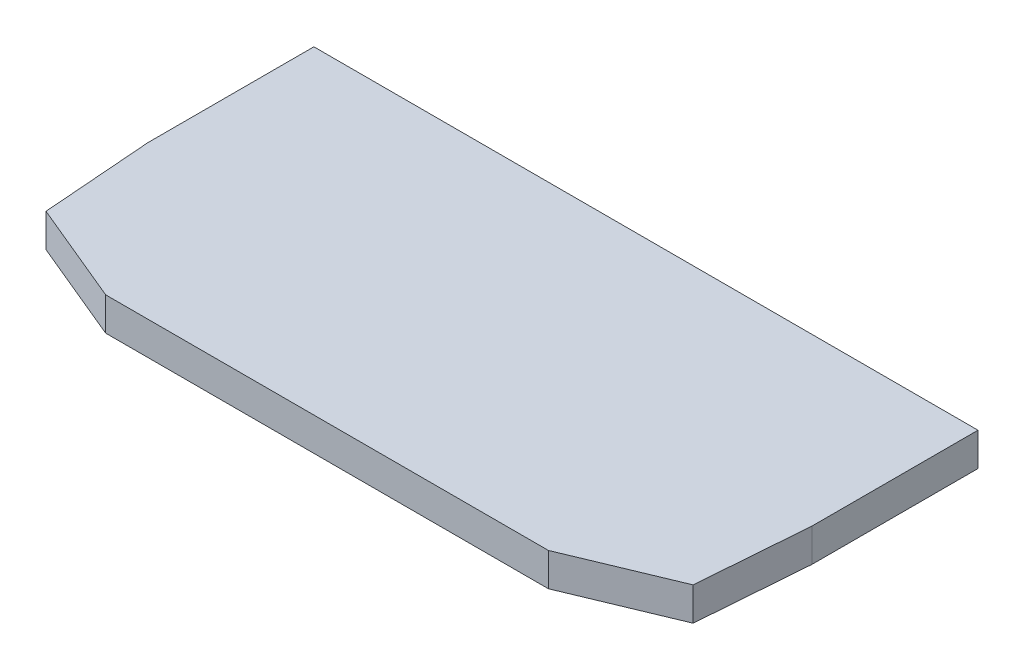
SolidWorks part; units mm, degrees
ref_plane "Front Plane" through (0, 0, 0) normal (0, 0, 1) x (1, 0, 0)
ref_plane "Top Plane" through (0, 0, 0) normal (0, 1, 0) x (1, 0, 0)
ref_plane "Right Plane" through (0, 0, 0) normal (1, 0, 0) x (0, 0, -1)
sketch "Sketch3" plane through (0, 0, 0) normal (0, 1, 0) x (1, 0, 0)
  line L0 (-27.1418, 11.12) -> (32.8582, 11.12)
  line L1 (32.8582, 11.12) -> (32.8582, -3.88)
  line L2 (-27.1418, 11.12) -> (-27.1418, -3.88)
  line L3 (-27.1418, -3.88) -> (-26.3741, -13.8504)
  line L4 (-26.3741, -13.8504) -> (-17.1418, -17.6929)
  line L5 (-17.1418, -17.6929) -> (22.8582, -17.6929)
  line L6 (22.8582, -17.6929) -> (32.0905, -13.8504)
  line L7 (32.0905, -13.8504) -> (32.8582, -3.88)
  dimension "D1" = 60
  dimension "D2" = 15
  dimension "D3" = 10
  dimension "D4" = 15
  dimension "D5" = 10
  dimension "D6" = 10
  dimension "D7" = 10
  dimension "D8" = 40
  dimension "D9" = 117
  dimension "D10" = 117
extrude "Boss-Extrude1" add sketch "Sketch3" along normal blind 3 contours L0 L1 L7 L6 L5 L4 L3 L2
ref_plane "Plane1" through (32.858, 0, 0) normal (1, 0, 0) x (0, 0, -1)
